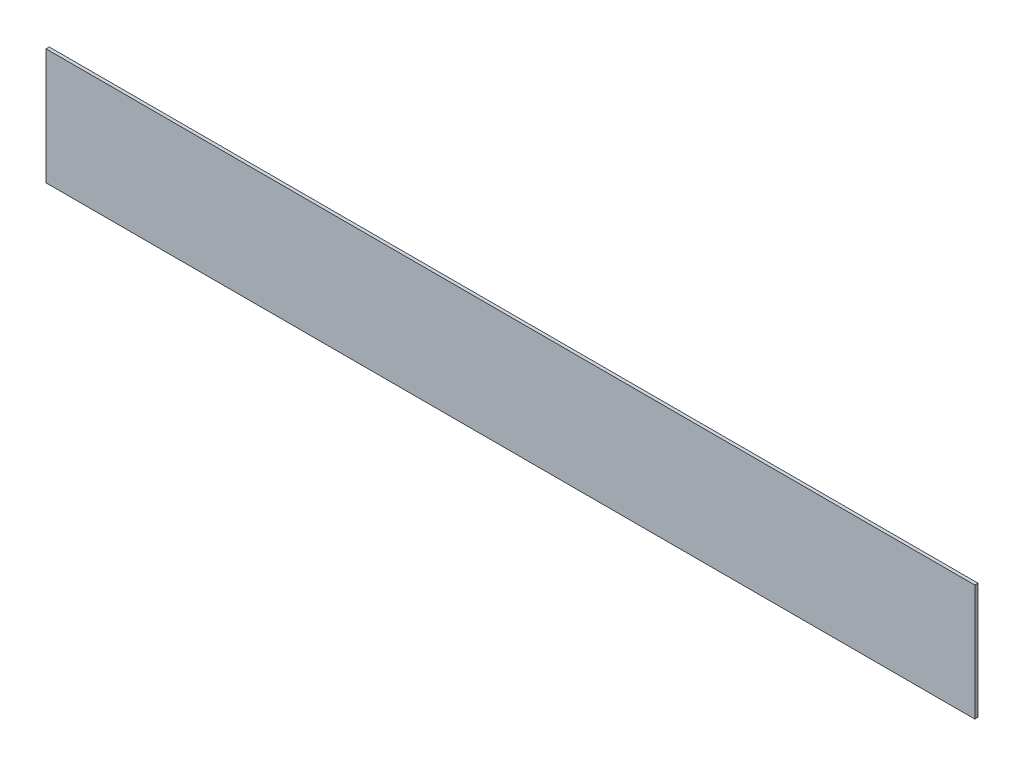
SolidWorks part; units mm, degrees
ref_plane "Front Plane" through (0, 0, 0) normal (0, 0, 1) x (1, 0, 0)
ref_plane "Top Plane" through (0, 0, 0) normal (0, 1, 0) x (1, 0, 0)
ref_plane "Right Plane" through (0, 0, 0) normal (1, 0, 0) x (0, 0, -1)
sketch "Sketch1" plane through (0, 0, 0) normal (0, 0, 1) x (1, 0, 0)
  line L1 (0, 0) -> (914.4, 0)
  line L2 (0, 0) -> (0, 114.3)
  line L3 (0, 114.3) -> (914.4, 114.3)
  line L4 (914.4, 0) -> (914.4, 114.3)
  dimension "D1" = 914.4
  dimension "D2" = 114.3
extrude "Boss-Extrude1" add sketch "Sketch1" along normal blind 3.175
